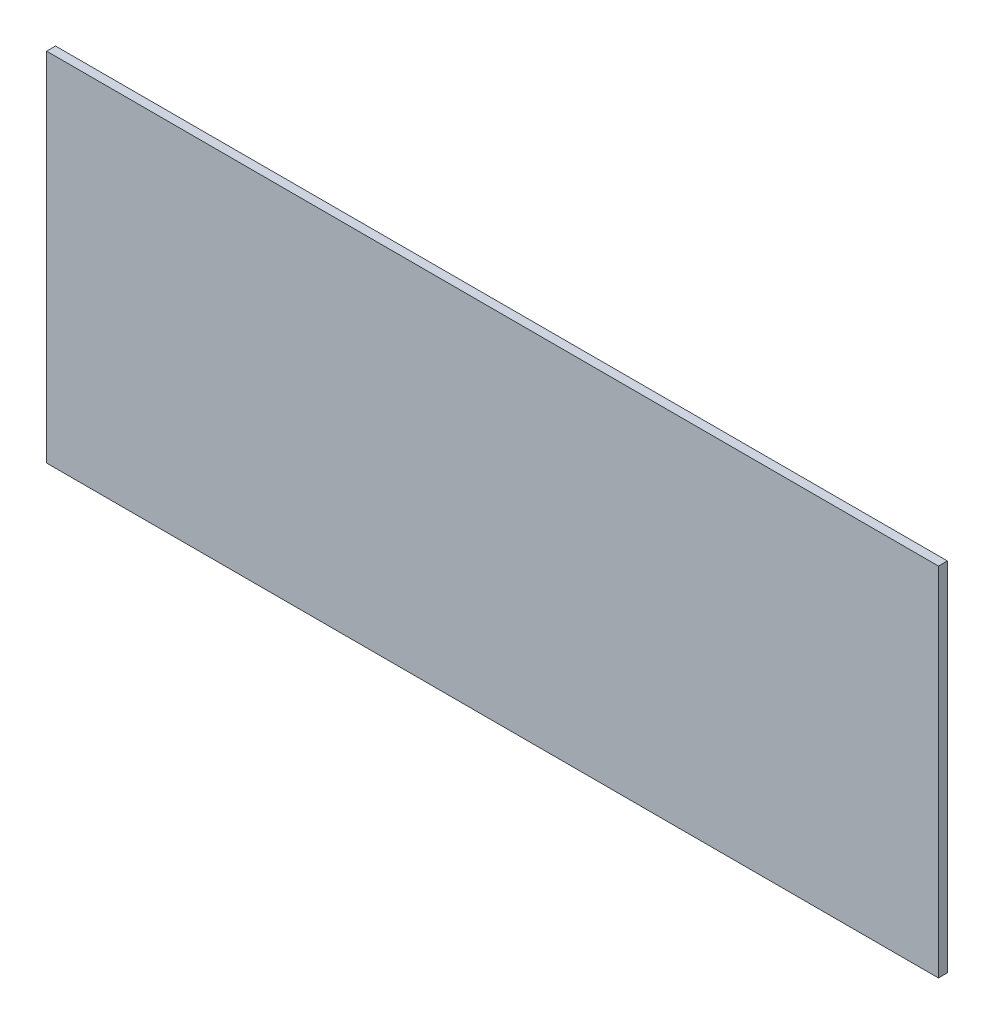
SolidWorks part; units mm, degrees
ref_plane "Front Plane" through (0, 0, 0) normal (0, 0, 1) x (1, 0, 0)
ref_plane "Top Plane" through (0, 0, 0) normal (0, 1, 0) x (1, 0, 0)
ref_plane "Right Plane" through (0, 0, 0) normal (1, 0, 0) x (0, 0, -1)
sketch "Sketch1" plane through (0, 0, 0) normal (0, 0, 1) x (1, 0, 0)
  line L1 (0, 0) -> (300, 0)
  line L2 (0, 0) -> (0, 120)
  line L3 (0, 120) -> (300, 120)
  line L4 (300, 0) -> (300, 120)
  dimension "D1" = 300
  dimension "D2" = 120
extrude "Boss-Extrude1" add sketch "Sketch1" along normal blind 3
